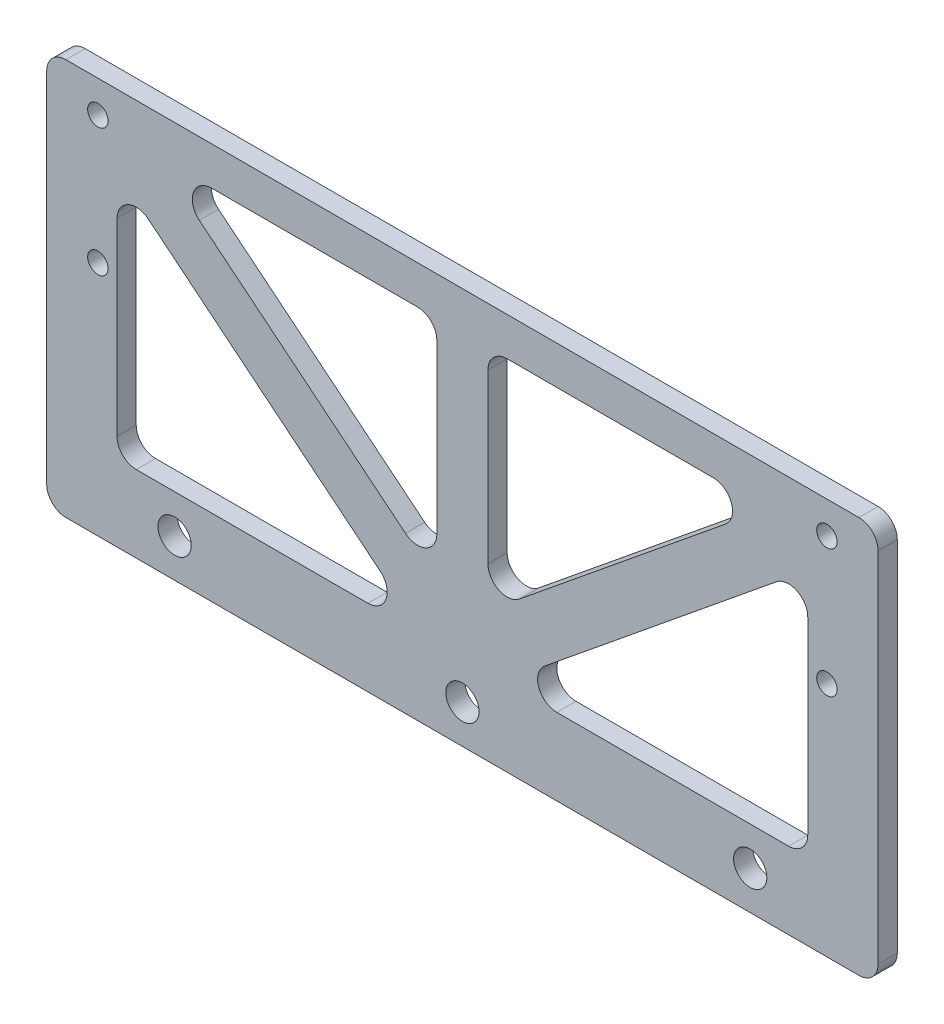
SolidWorks part; units mm, degrees
material "Thornel Mat VMA"
ref_plane "前视基准面" through (0, 0, 0) normal (0, 0, 1) x (1, 0, 0)
ref_plane "上视基准面" through (0, 0, 0) normal (0, 1, 0) x (1, 0, 0)
ref_plane "右视基准面" through (0, 0, 0) normal (1, 0, 0) x (0, 0, -1)
sketch "草图1" plane through (0, 0, 0) normal (0, 0, 1) x (1, 0, 0)
  line L1 (-65, 31) -> (65, 31)
  line L2 (-65, 31) -> (-65, -31)
  line L3 (-65, -31) -> (65, -31)
  line L4 (65, 31) -> (65, -31)
  line L5 (-65, 31) -> (65, -31) construction
  line L6 (-65, -31) -> (65, 31) construction
  point P0 (0, 0)
  dimension "D1" = 130
  dimension "D2" = 62
extrude "凸台-拉伸1" add sketch "草图1" along normal blind 3
sketch "草图2" plane through (0, 0, 3) normal (0, 0, 1) x (1, 0, 0)
  line L0 (-45, -25) -> (45, -25) construction
  line L1 (-65, -31) -> (65, -31) construction
  circle A0 centre (-45, -25) radius 2.6
  circle A1 centre (0, -25) radius 2.6
  circle A2 centre (45, -25) radius 2.6
  point P4 (0, -25)
  dimension "D3" = 5.2
  dimension "D1" = 6
  dimension "D2" = 90
extrude "切除-拉伸1" cut sketch "草图2" against normal through all
sketch "草图3" plane through (0, 0, 3) normal (0, 0, 1) x (1, 0, 0)
  line L0 (57, 26) -> (57, 6) construction
  line L1 (65, -31) -> (65, 31) construction
  line L2 (65, 31) -> (-65, 31) construction
  circle A0 centre (57, 26) radius 1.6
  circle A1 centre (57, 6) radius 1.6
  dimension "D4" = 3.2
  dimension "D1" = 20
  dimension "D2" = 8
  dimension "D3" = 5
extrude "切除-拉伸2" cut sketch "草图3" against normal through all
mirror "镜向1" about plane through (0, 0, 0) normal (1, 0, 0) of "切除-拉伸2"
sketch "草图4" plane through (0, 0, 3) normal (0, 0, 1) x (1, 0, 0)
  line L0 (-65, 31) -> (-65, -31) construction
  line L1 (-65, 31) -> (65, 31)
  line L2 (-65, 31) -> (-65, -31)
  line L3 (-65, -31) -> (65, -31)
  line L4 (65, 31) -> (65, -31)
  line L5 (-65, -31) -> (65, -31) construction
  line L6 (-54, 25) -> (0, -19)
  line L7 (-54, 25) -> (54, 25)
  line L8 (-54, 25) -> (-54, -19)
  line L9 (-54, -19) -> (54, -19)
  line L10 (54, 25) -> (54, -19)
  line L11 (0, -19) -> (54, 25)
  line L12 (0, 25) -> (0, -19)
  line L13 (-4, 25) -> (-4, -19)
  line L14 (-56.5267, 21.8991) -> (-2.5267, -22.1009)
  line L15 (2.5267, -22.1009) -> (56.5267, 21.8991)
  line L16 (4, 25) -> (4, -19)
  line L17 (-51.4733, 28.1009) -> (2.5267, -15.8991)
  line L18 (-2.5267, -15.8991) -> (51.4733, 28.1009)
  dimension "D1" = 11
  dimension "D2" = 11
  dimension "D3" = 6
  dimension "D4" = 12
  dimension "D5" = 4
  dimension "D6" = 4
extrude "切除-拉伸3" cut sketch "草图4" against normal through all contours L14 L8 L9 | L7 L17 L13 | L16 L18 L7 | L15 L9 L10
fillet "圆角1" radius 3 12 edges at (-4, 25, 1.5) (-4, -10.581, 1.5) (-47.6676, 25, 1.5) (47.6676, 25, 1.5) (4, -10.581, 1.5) (4, 25, 1.5) (-6.3324, -19, 1.5) (-54, 19.8403, 1.5) (54, 19.8403, 1.5) (6.3324, -19, 1.5) (54, -19, 1.5) (-54, -19, 1.5)
fillet "圆角2" radius 3 4 edges at (65, -31, 1.5) (-65, -31, 1.5) (65, 31, 1.5) (-65, 31, 1.5)
